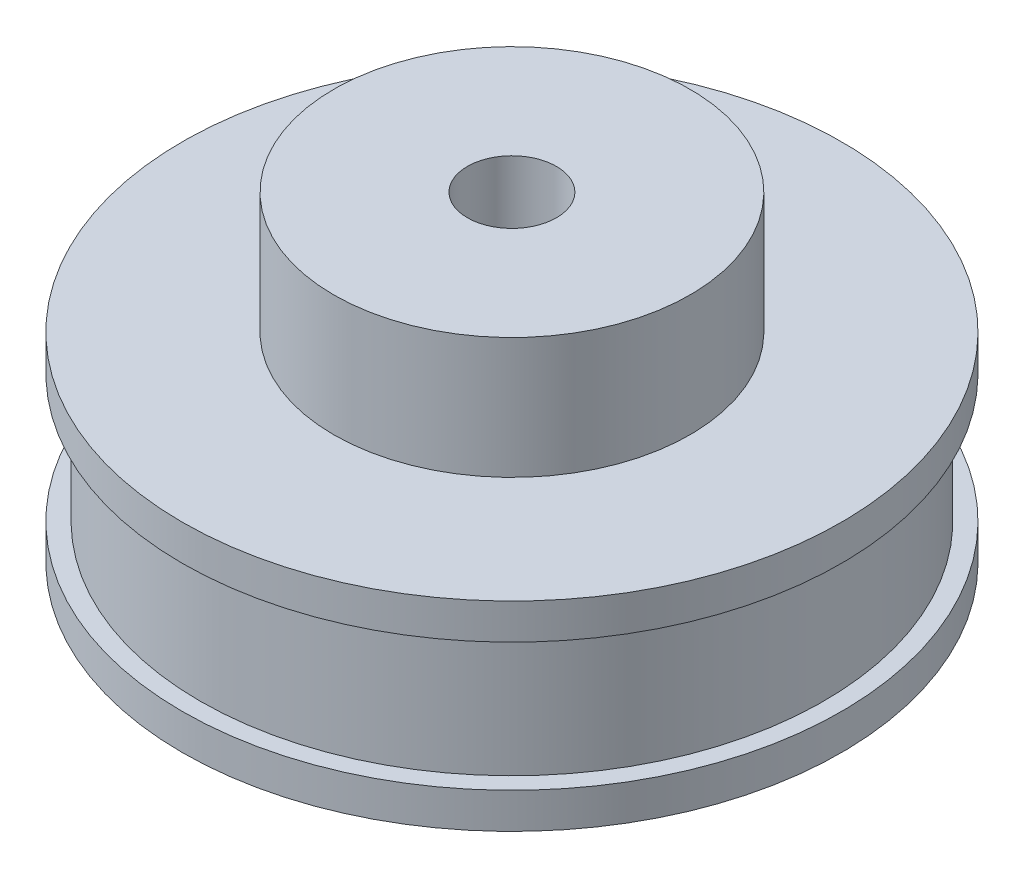
SolidWorks part; units mm, degrees
ref_plane "Ebene vorne" through (0, 0, 0) normal (0, 0, 1) x (1, 0, 0)
ref_plane "Ebene oben" through (0, 0, 0) normal (0, 1, 0) x (1, 0, 0)
ref_plane "Ebene rechts" through (0, 0, 0) normal (1, 0, 0) x (0, 0, -1)
sketch "Skizze1" plane through (0, 0, 0) normal (0, 1, 0) x (1, 0, 0)
  circle A0 centre (0, 0) radius 18.5
  dimension "D1" = 37
extrude "Aufsatz-Linear austragen1" add sketch "Skizze1" along normal blind 2
sketch "Skizze2" plane through (0, 2, 0) normal (0, 1, 0) x (1, 0, 0)
  circle A0 centre (0, 0) radius 17.5
  dimension "D1" = 35
extrude "Aufsatz-Linear austragen2" add sketch "Skizze2" along normal blind 7.2
sketch "Skizze3" plane through (0, 9.2, 0) normal (0, 1, 0) x (1, 0, 0)
  circle A0 centre (0, 0) radius 18.5
extrude "Aufsatz-Linear austragen3" add sketch "Skizze3" along normal blind 2
sketch "Skizze4" plane through (0, 11.2, 0) normal (0, 1, 0) x (1, 0, 0)
  circle A0 centre (0, 0) radius 10
  dimension "D1" = 20
extrude "Aufsatz-Linear austragen4" add sketch "Skizze4" along normal blind 6.8
sketch "Skizze5" plane through (0, 18, 0) normal (0, 1, 0) x (1, 0, 0)
  circle A0 centre (0, 0) radius 2.5
  dimension "D1" = 5
extrude "Schnitt-Linear austragen1" cut sketch "Skizze5" against normal through all
